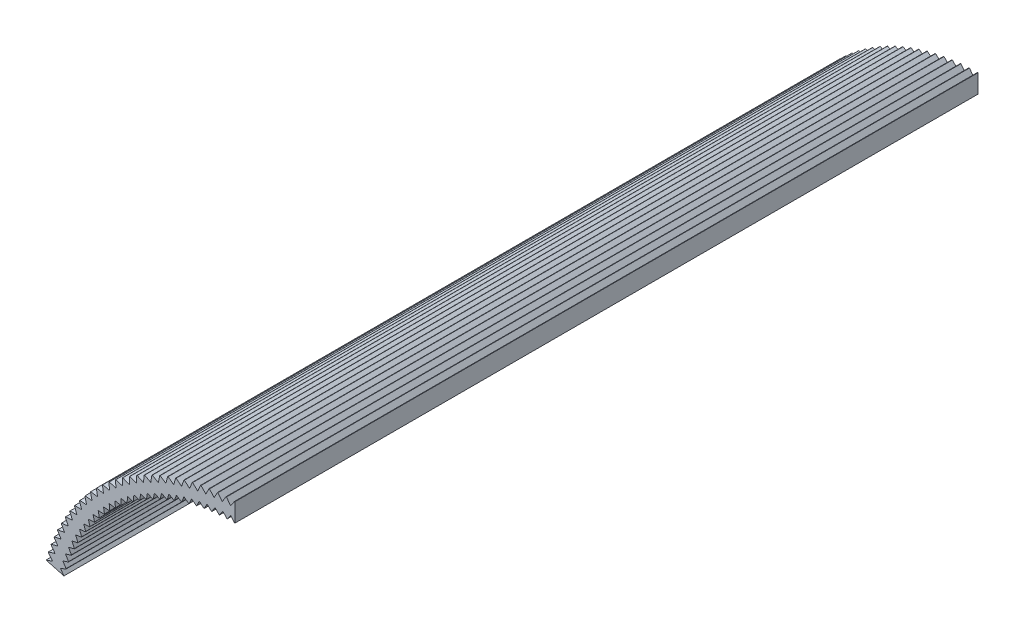
SolidWorks part; units mm, degrees
ref_plane "Front Plane" through (0, 0, 0) normal (0, 0, 1) x (1, 0, 0)
ref_plane "Top Plane" through (0, 0, 0) normal (0, 1, 0) x (1, 0, 0)
ref_plane "Right Plane" through (0, 0, 0) normal (1, 0, 0) x (0, 0, -1)
sketch "Sketch1" plane through (0, 0, 0) normal (0, 0, 1) x (1, 0, 0)
  line L0 (0, 158) -> (0, 0) construction
  line L1 (0, 0) -> (-152.6163, 40.8934) construction
  line L2 (0, 143) -> (0, 158)
  line L3 (-152.6163, 40.8934) -> (-138.1274, 37.0111)
  arc A0 (0, 158) -> (-152.6163, 40.8934) centre (0, 0) ccw
  arc A1 (0, 143) -> (-138.1274, 37.0111) centre (0, 0) ccw
  dimension "D3" = 15
  dimension "D1" = 158
  dimension "D2" = 75
extrude "Boss-Extrude1" add sketch "Sketch1" along normal mid plane 600
sketch "Sketch2" plane through (0, 0, 0) normal (0, 0, 1) x (1, 0, 0)
  line L0 (-152.6163, 40.8934) -> (-147.295, 42.735)
  line L1 (-147.295, 42.735) -> (-150.8043, 47.1387)
  line L2 (0, 0) -> (-151.7424, 44.0254) construction
  line L3 (-138.1274, 37.0111) -> (-140.9475, 40.8934)
  line L4 (-140.9475, 40.8934) -> (-136.4875, 42.6635)
  line L7 (-152.6163, 40.8934) -> (-138.1274, 37.0111)
  line L8 (0, 143) -> (0, 158)
  line L9 (-152.6163, 40.8934) -> (-138.1274, 37.0111)
  line L10 (0, 143) -> (0, 158)
  arc A0 (0, 158) -> (-152.6163, 40.8934) centre (0, 0) ccw construction
  arc A1 (0, 143) -> (-138.1274, 37.0111) centre (0, 0) ccw construction
  arc A4 (0, 158) -> (-152.6163, 40.8934) centre (0, 0) ccw
  arc A5 (0, 143) -> (-138.1274, 37.0111) centre (0, 0) ccw
  arc A6 (0, 158) -> (-152.6163, 40.8934) centre (0, 0) ccw
  arc A7 (0, 143) -> (-138.1274, 37.0111) centre (0, 0) ccw
  dimension "D1" = 0
  dimension "D2" = 0
extrude "Cut-Extrude1" cut sketch "Sketch2" against normal mid plane 610 contours L2 L1 A6 | L0 L2 A6 | A7 L2 L3 | L2 A7 L4
ref_point "Point1"
pattern_circular "CirPattern1" count 31 over 75 about axis through (0, 0, 0) along (0, 0, 1) of "Cut-Extrude1"
